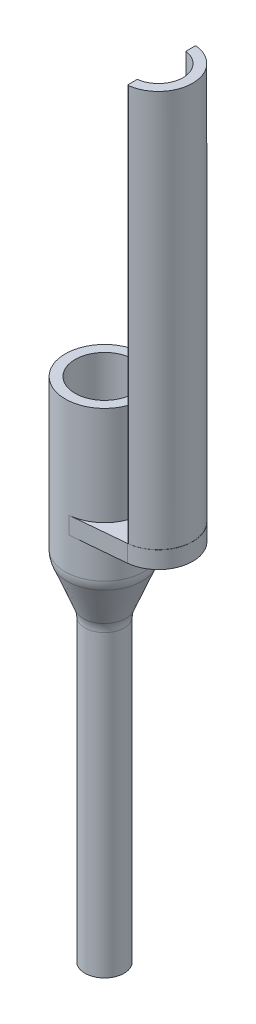
SolidWorks part; units mm, degrees
material "ABS"
ref_plane "Front" through (0, 0, 0) normal (0, 0, 1) x (1, 0, 0)
ref_plane "Top" through (0, 0, 0) normal (0, 1, 0) x (1, 0, 0)
ref_plane "Right" through (0, 0, 0) normal (1, 0, 0) x (0, 0, -1)
sketch "Эскиз1" plane through (0, 0, 0) normal (0, 0, 1) x (1, 0, 0)
  line L8 (0, -1000) -> (0, 49000) construction
  line L10 (8, 23.5) -> (8, -8)
  line L11 (8, -8) -> (4, -18)
  line L12 (4, -18) -> (4, -80)
  line L17 (3.1, -80) -> (4, -80)
  line L28 (3.1, -8) -> (6, -8)
  line L29 (6, 23.5) -> (6, -8)
  line L30 (3.1, -80) -> (3.1, -8)
  line L31 (6, 23.5) -> (8, 23.5)
  dimension "D1" = 80
  dimension "D2" = 23.5
  dimension "D3" = 6.2
  dimension "D4" = 8
  dimension "D5" = 16
  dimension "D6" = 2
  dimension "D7" = 31.5
  dimension "D8" = 62
  dimension "D9" = 8
revolve "Повернуть1" add sketch "Эскиз1" angle 360 about L8
fillet "Скругление1" radius 5 2 edges at (8, -8, 0) (4, -18, 0)
ref_plane "Плоскость1" through (0, 3.3, 0) normal (0, 1, 0) x (1, 0, 0)
sketch "Эскиз2" plane through (0, 3.3, 0) normal (0, 1, 0) x (1, 0, 0)
  line L0 (11.6394, 6.971) -> (0.7271, 7.9669)
  line L1 (0.7271, -7.9669) -> (11.6394, -6.971)
  arc A0 (0.7271, -7.9669) -> (0.7271, 7.9669) centre (0, 0) ccw
  arc A1 (11.6394, -6.971) -> (11.6394, 6.971) centre (11.0032, 0) ccw
  arc A2 (0.7271, 7.9669) -> (0.7271, -7.9669) centre (0, 0) ccw construction
  dimension "D1" = 14
extrude "Бобышка-Вытянуть1" add sketch "Эскиз2" against normal blind 4
chamfer "Фаска1" distance 3 distance2 0.5 3 edges at (6.1832, -0.7, 7.469) (6.1832, -0.7, -7.469) (18.0032, -0.7, 0)
sketch "Эскиз3" plane through (0, 3.3, 0) normal (0, 1, 0) x (1, 0, 0)
  line L0 (11.6404, 4.9592) -> (11.6394, 6.971)
  line L2 (11.6401, -4.9593) -> (11.6394, -6.971)
  arc A2 (11.6394, -6.971) -> (11.6394, 6.971) centre (10.9758, 0) ccw
  arc A3 (11.4576, -4.9793) -> (11.4576, 4.9793) centre (11.0032, 0) ccw
  arc A4 (11.6401, -4.9593) -> (11.6404, 4.9592) centre (11.0032, 0) ccw
  dimension "D1" = 2
extrude "Бобышка-Вытянуть2" add sketch "Эскиз3" along normal blind 81
fillet "Скругление2" radius 0.2 2 edges at (11.6394, 43.8, -6.971) (11.6394, 43.8, 6.971)
